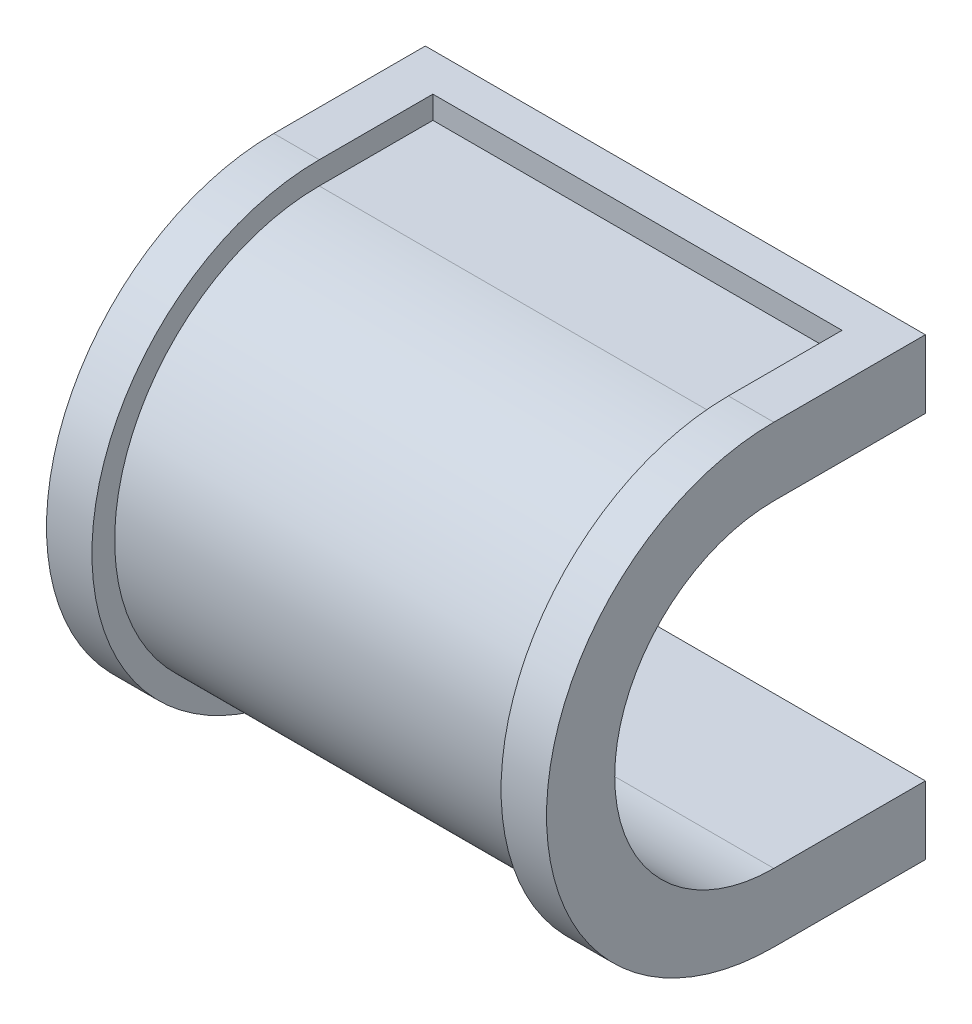
SolidWorks part; units mm, degrees
ref_plane "Front Plane" through (0, 0, 0) normal (1, 0, 0) x (0, 1, 0)
ref_plane "Top Plane" through (0, 0, 0) normal (0, 0, 1) x (0, 1, 0)
ref_plane "Right Plane" through (0, 0, 0) normal (0, 1, 0) x (-1, 0, 0)
sketch "Sketch1" plane through (0, 0, 0) normal (1, 0, 0) x (0, 1, 0)
  line L1 (0, 0) -> (0, -15)
  line L2 (0, -20) -> (54, -20)
  line L3 (54, -15) -> (54, 0)
  line L4 (54, -20) -> (57, -20)
  line L5 (57, -20) -> (57, -15)
  line L6 (57, -15) -> (54, -15)
  line L7 (0, -20) -> (-3, -20)
  line L8 (-3, -20) -> (-3, -15)
  line L9 (-3, -15) -> (0, -15)
  arc A0 (0, 0) -> (54, 0) centre (27, 0) cw
  dimension "D1" = 54
  dimension "D2" = 20
  dimension "D3" = 5
  dimension "D4" = 5
  dimension "D5" = 3
  dimension "D6" = 3
extrude "Boss-Extrude1" add sketch "Sketch1" along normal blind 66
sketch "Sketch2" plane through (66, 0, 0) normal (1, 0, 0) x (0, 1, 0)
  line L1 (6, -20) -> (6, 27.3392) construction
  line L3 (48, -20) -> (48.4264, 27.3392) construction
  line L6 (-3, -20) -> (57, -20) construction
  line L9 (6, 0) -> (6, -20)
  line L10 (48, 0) -> (48, -20)
  line L11 (6, -20) -> (48, -20)
  arc A3 (48, 0) -> (6, 0) centre (27, 0) ccw
  arc A4 (48, 0) -> (6, 0) centre (27, 0) ccw
  dimension "D1" = 6
extrude "Cut-Extrude1" cut sketch "Sketch2" against normal through all
sketch "Sketch3" plane through (66, 0, 0) normal (1, 0, 0) x (0, 1, 0)
  line L3 (-3, -15) -> (0, -15)
  line L4 (0, -15) -> (0, 0)
  line L5 (57, -15) -> (57, 0)
  line L6 (-3, 0) -> (-3, -15)
  line L7 (57, -15) -> (57, 0)
  line L8 (-3, 0) -> (-3, -15)
  line L9 (57, -15) -> (54, -15)
  line L10 (54, -15) -> (54, 0)
  arc A3 (0, 0) -> (54, 0) centre (27, 0) cw
  arc A4 (57, 0) -> (-3, 0) centre (27, 0) ccw
  arc A5 (57, 0) -> (-3, 0) centre (27, 0) ccw
  dimension "D1" = 3
extrude "Boss-Extrude2" add sketch "Sketch3" against normal blind 6
sketch "Sketch4" plane through (0, 0, 0) normal (-1, 0, 0) x (0, -1, 0)
  line L0 (-54, -15) -> (-57, -15)
  line L1 (-57, -15) -> (-57, 0)
  line L2 (-54, -15) -> (-54, 0)
  line L3 (0, 0) -> (0, -15)
  line L4 (0, -15) -> (3, -15)
  line L5 (3, -15) -> (3, 0)
  arc A0 (-57, 0) -> (3, 0) centre (-27, 0) cw
  arc A1 (-54, 0) -> (0, 0) centre (-27, 0) cw
extrude "Boss-Extrude3" add sketch "Sketch4" against normal blind 6
